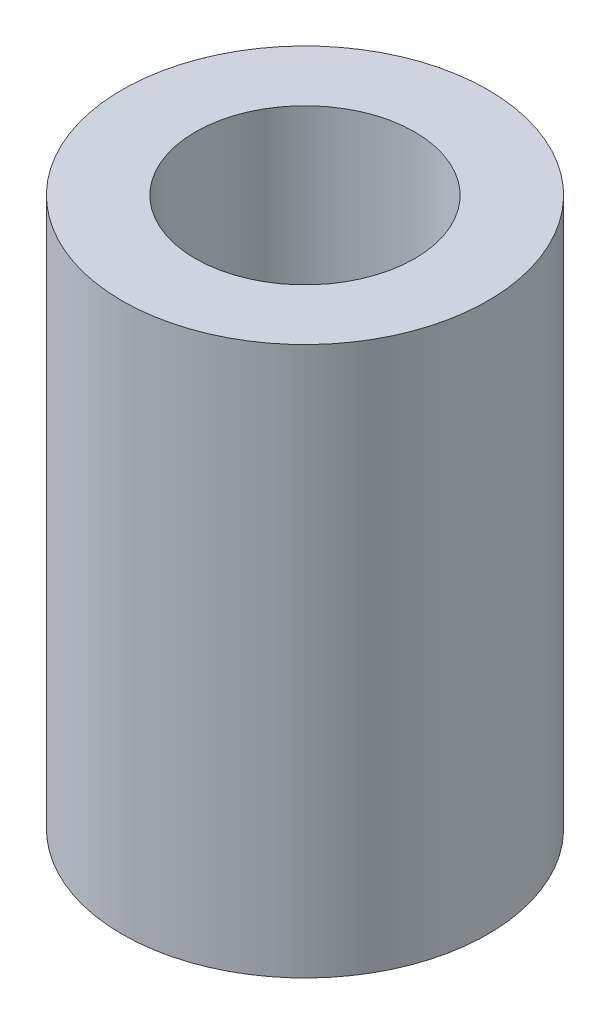
SolidWorks part; units mm, degrees
ref_plane "Front Plane" through (0, 0, 0) normal (0, 0, 1) x (1, 0, 0)
ref_plane "Top Plane" through (0, 0, 0) normal (0, 1, 0) x (1, 0, 0)
ref_plane "Right Plane" through (0, 0, 0) normal (1, 0, 0) x (0, 0, -1)
sketch "Sketch1" plane through (0, 0, 0) normal (0, 1, 0) x (1, 0, 0)
  circle A0 centre (0, 0) radius 10
  dimension "D1" = 20
extrude "Boss-Extrude1" add sketch "Sketch1" along normal blind 30
sketch "Sketch2" plane through (0, 30, 0) normal (0, 1, 0) x (1, 0, 0)
  circle A0 centre (0, 0) radius 6
  dimension "D1" = 12
extrude "Cut-Extrude1" cut sketch "Sketch2" against normal blind 10
sketch "Sketch3" plane through (0, 0, 0) normal (0, -1, 0) x (1, 0, 0)
  circle A0 centre (0, 0) radius 5
  dimension "D1" = 10
extrude "Cut-Extrude2" cut sketch "Sketch3" against normal blind 10
